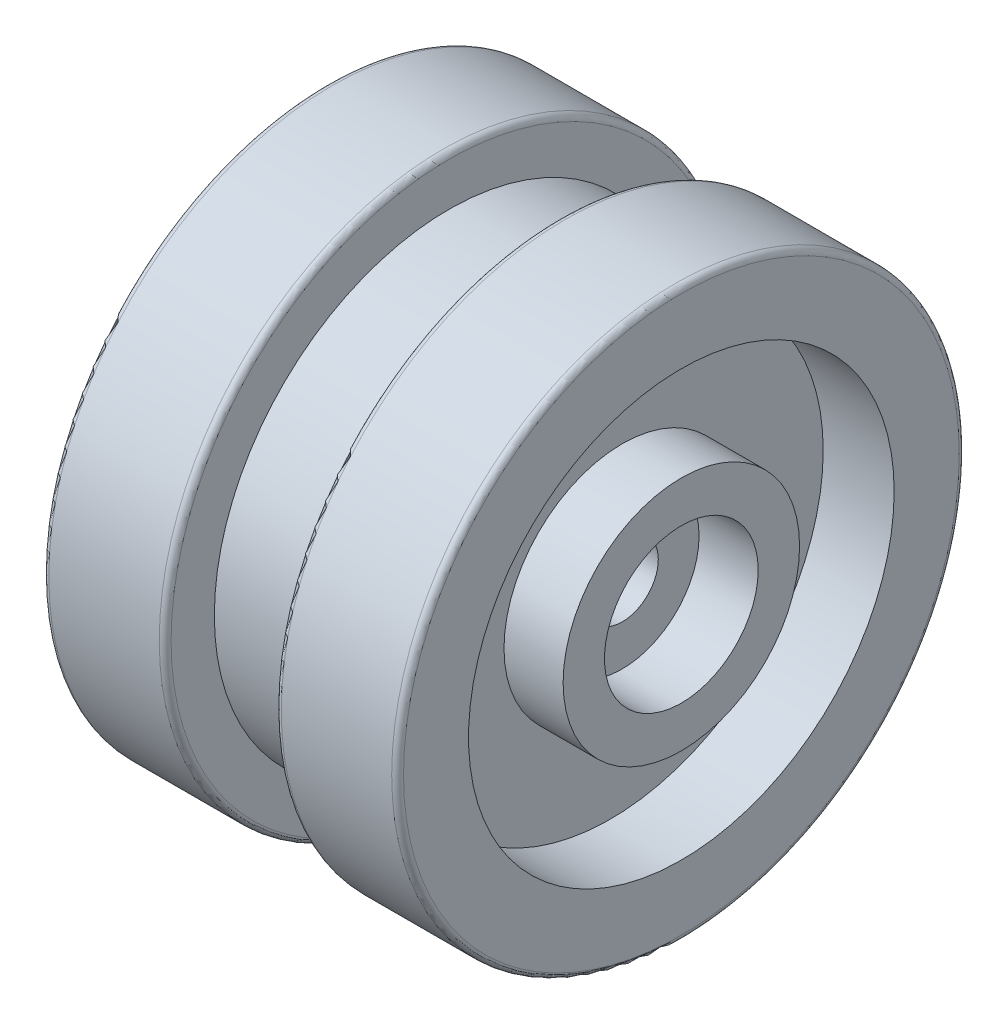
SolidWorks part; units mm, degrees
ref_plane "Front Plane" through (0, 0, 0) normal (0, 0, 1) x (1, 0, 0)
ref_plane "Top Plane" through (0, 0, 0) normal (0, 1, 0) x (1, 0, 0)
ref_plane "Right Plane" through (0, 0, 0) normal (1, 0, 0) x (0, 0, -1)
sketch "Sketch2" plane through (0, 0, 0) normal (0, 0, 1) x (1, 0, 0)
  line L0 (-2.0852, 1.3557) -> (7.2348, 1.3557)
  line L1 (-2.0852, 1.3557) -> (-2.0852, 5.5157)
  line L2 (7.2348, 1.3557) -> (7.2348, 5.5157)
  line L3 (7.2348, 5.5157) -> (17.5748, 5.5157)
  line L4 (-2.0852, 5.5157) -> (-12.4252, 5.5157)
  line L5 (-12.4252, 5.5157) -> (-12.4252, -18.4843)
  line L6 (-12.4252, -18.4843) -> (17.5748, -18.4843)
  line L7 (17.5748, -18.4843) -> (17.5748, 5.5157)
  line L8 (-12.4252, -18.4843) -> (27.3603, -18.4843) construction
  dimension "D1" = 30
  dimension "D2" = 24
  dimension "D4" = 4.16
  dimension "D5" = 9.32
revolve "Revolve1" add sketch "Sketch2" angle 360 about L8
sketch "Sketch3" plane through (17.5748, 0, 0) normal (1, 0, 0) x (0, 0, -1)
  circle A0 centre (0, -18.4843) radius 2
extrude "Cut-Extrude1" cut sketch "Sketch3" against normal through all
fillet "Fillet2" radius 0.5 4 edges at (-2.0852, -18.4843, 24) (7.2348, -18.4843, 24) (17.5748, -18.4843, 24) (-12.4252, -18.4843, 24)
sketch "Sketch4" plane through (17.5748, 0, 0) normal (1, 0, 0) x (0, 0, -1)
  circle A0 centre (0, -18.4843) radius 6
  circle A1 centre (0, -18.4843) radius 18
extrude "Cut-Extrude2" cut sketch "Sketch4" against normal blind 6
sketch "Sketch5" plane through (-12.4252, 0, 0) normal (-1, 0, 0) x (0, 0, 1)
  circle A0 centre (0, -18.4843) radius 6
  circle A1 centre (0, -18.4843) radius 18
extrude "Cut-Extrude3" cut sketch "Sketch5" against normal blind 6 contours A1
sketch "Sketch6" plane through (-6.4252, 0, 0) normal (-1, 0, 0) x (0, 0, 1)
  circle A0 centre (0, -18.4843) radius 10
extrude "Boss-Extrude1" add sketch "Sketch6" along normal through all
sketch "Sketch7" plane through (-12.4252, 0, 0) normal (-1, 0, 0) x (0, 0, 1)
  circle A0 centre (0, -18.4843) radius 3.05
  dimension "D1" = 6.1
sketch "Sketch8" plane through (17.5748, 0, 0) normal (1, 0, 0) x (0, 0, -1)
  circle A0 centre (0, -18.4843) radius 8
extrude "Boss-Extrude2" add sketch "Sketch8" against normal blind 10 contours A0
sketch "Sketch9" plane through (17.5748, 0, 0) normal (1, 0, 0) x (0, 0, -1)
  circle A0 centre (0, -18.4843) radius 6.5
sketch "Sketch10" plane through (-12.4252, 0, 0) normal (-1, 0, 0) x (0, 0, 1)
  circle A0 centre (0, -18.4843) radius 6.5
extrude "Cut-Extrude5" cut sketch "Sketch10" against normal blind 5 contours A0
sketch "Sketch11" plane through (17.5748, 0, 0) normal (1, 0, 0) x (0, 0, -1)
  circle A0 centre (0, -18.4843) radius 10
extrude "Boss-Extrude3" add sketch "Sketch11" against normal blind 5
sketch "Sketch12" plane through (17.5748, 0, 0) normal (1, 0, 0) x (0, 0, -1)
  circle A0 centre (0, -18.4843) radius 6.5
extrude "Cut-Extrude6" cut sketch "Sketch12" against normal blind 5
extrude "Cut-Extrude8" cut sketch "Sketch7" against normal through all contours A0
ref_plane "Plane1" through (0, 0, -19.84) normal (0, 0, -1) x (-1, 0, 0)
sketch "Sketch13" plane through (0, 0, -19.84) normal (0, 0, -1) x (-1, 0, 0)
  line L0 (2.0852, 1.3557) -> (2.0852, -38.3243) construction
  line L1 (-7.2348, -38.3243) -> (-7.2348, 1.3557) construction
  line L2 (2.0852, 1.3557) -> (2.0852, -38.3243)
  line L3 (-7.2348, -38.3243) -> (-7.2348, 1.3557)
  line L4 (-2.5748, 1.3557) -> (-2.5748, -38.3243) construction
  dimension "D1" = 4.66
